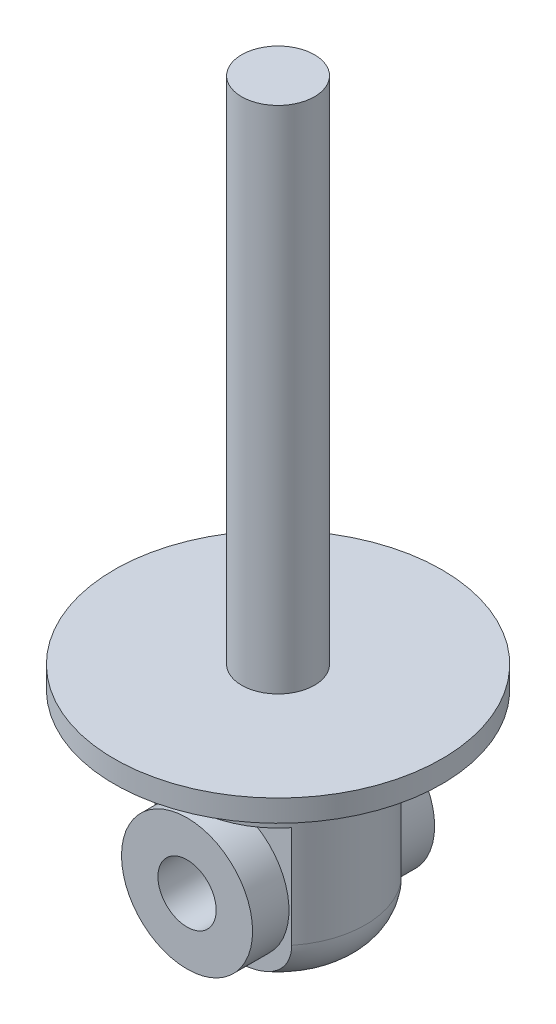
SolidWorks part; units mm, degrees
ref_plane "Piano frontale" through (0, 0, 0) normal (0, 0, 1) x (1, 0, 0)
ref_plane "Piano superiore" through (0, 0, 0) normal (0, 1, 0) x (1, 0, 0)
ref_plane "Piano destro" through (0, 0, 0) normal (1, 0, 0) x (0, 0, -1)
sketch "Schizzo1" plane through (0, 0, 0) normal (1, 0, 0) x (0, 0, -1)
  line L1 (0, 70) -> (5, 70)
  line L2 (0, 70) -> (0, 0)
  line L3 (0, 0) -> (5, 0)
  line L4 (5, 70) -> (5, 0)
  dimension "D1" = 5
  dimension "D2" = 70
revolve "Rivoluzione1" add sketch "Schizzo1" angle 360 about L2
sketch "Schizzo2" plane through (0, 0, 0) normal (0, -1, 0) x (1, 0, 0)
  circle A0 centre (0, 0) radius 22.5
  dimension "D1" = 45
extrude "Estrusione-Estrusione1" add sketch "Schizzo2" along normal blind 3
sketch "Schizzo4" plane through (0, 0, 0) normal (0, 0, 1) x (1, 0, 0)
  line L5 (-22.5, -3) -> (22.5, -3) construction
  line L6 (0, -3) -> (12, -3)
  line L7 (0, -3) -> (0, -31)
  line L8 (0, -31) -> (6, -31)
  line L9 (12, -3) -> (12, -25)
  arc A0 (6, -31) -> (12, -25) centre (6, -25) ccw
  point P11 (12, -31)
  dimension "D3" = 6
  dimension "D1" = 12
  dimension "D2" = 28
revolve "Rivoluzione2" add sketch "Schizzo4" angle 360 about L7
sketch "Schizzo5" plane through (0, 0, 0) normal (1, 0, 0) x (0, 0, -1)
  line L0 (12, -25) -> (12, -3) construction
  line L16 (-12, -11) -> (-7.5, -11)
  line L17 (-12, -11) -> (-12, -31)
  line L18 (-12, -31) -> (-7.5, -31)
  line L19 (-7.5, -11) -> (-7.5, -31)
  line L20 (12, -11) -> (7.5, -11)
  line L21 (12, -11) -> (12, -31)
  line L22 (12, -31) -> (7.5, -31)
  line L23 (7.5, -11) -> (7.5, -31)
  line L24 (-12, -3) -> (-12, -25) construction
  line L25 (-6, -31) -> (6, -31) construction
  line L26 (-12, -3) -> (12, -3) construction
  dimension "D1" = 8
  dimension "D2" = 15
extrude "Taglio-Estrusione1" cut sketch "Schizzo5" against normal through all both and the other way through all
sketch "Schizzo6" plane through (0, 0, 7.5) normal (0, 0, 1) x (1, 0, 0)
  line L0 (-12, -3) -> (12, -3) construction
  circle A0 centre (0, -21) radius 4
  dimension "D1" = 8
  dimension "D2" = 18
extrude "Taglio-Estrusione2" cut sketch "Schizzo6" against normal through all
sketch "Schizzo7" plane through (0, 0, 7.5) normal (0, 0, 1) x (1, 0, 0)
  circle A0 centre (0, -21) radius 4 construction
  circle A1 centre (0, -21) radius 4
  circle A2 centre (0, -21) radius 9
  dimension "D1" = 18
extrude "Estrusione-Estrusione2" add sketch "Schizzo7" along normal blind 5
mirror "Specchia1" about plane through (0, 0, 0) normal (0, 0, 1) of "Estrusione-Estrusione2"
